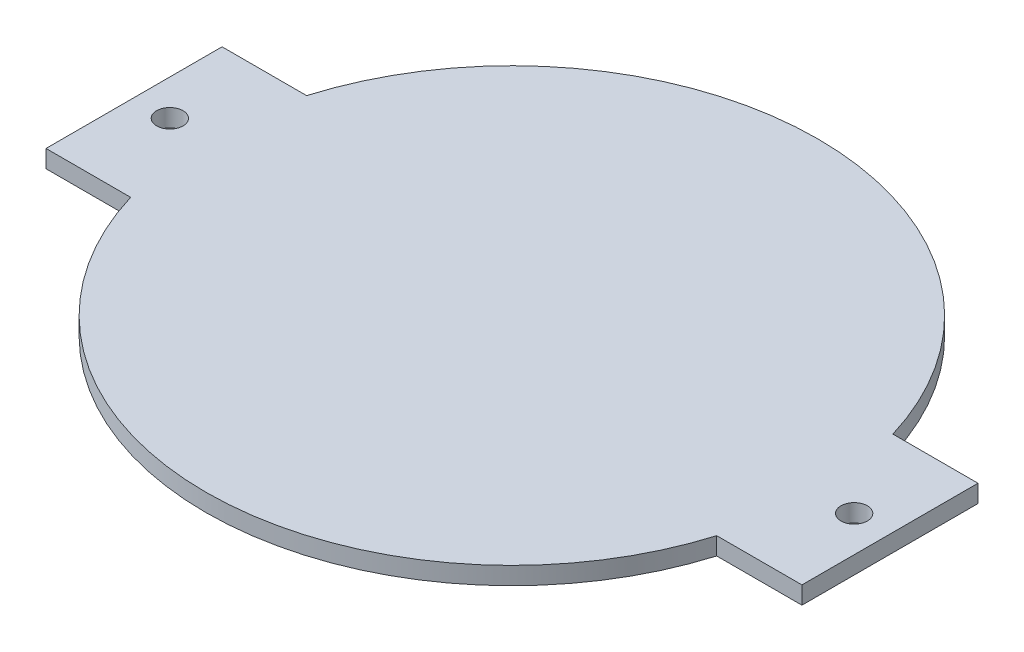
SolidWorks part; units mm, degrees
ref_plane "Front Plane" through (0, 0, 0) normal (0, 0, 1) x (1, 0, 0)
ref_plane "Top Plane" through (0, 0, 0) normal (0, 1, 0) x (1, 0, 0)
ref_plane "Right Plane" through (0, 0, 0) normal (1, 0, 0) x (0, 0, -1)
sketch "Sketch1" plane through (0, 0, 0) normal (0, 1, 0) x (0.9986, 0, -0.0537)
  line L0 (-66.8083, 7.0454) -> (-62.0146, 6.7879)
  line L1 (-23.9342, 4.7418) -> (-24.4707, -5.2438)
  line L2 (-67.3449, -2.9402) -> (-62.5451, -3.1981)
  line L3 (-23.9342, 4.7418) -> (-28.7631, 5.0013)
  line L4 (-66.8083, 7.0454) -> (-67.3449, -2.9402)
  line L5 (-24.4707, -5.2438) -> (-29.3057, -4.984)
  circle A0 centre (-65.045, 1.9435) radius 0.75
  circle A1 centre (-26.234, -0.1418) radius 0.75
  arc A2 (-28.7631, 5.0013) -> (-62.0146, 6.7879) centre (-45.6566, 0.9118) ccw
  arc A3 (-62.5451, -3.1981) -> (-29.3057, -4.984) centre (-45.6566, 0.9118) ccw
extrude "Boss-Extrude1" add sketch "Sketch1" along normal blind 1
